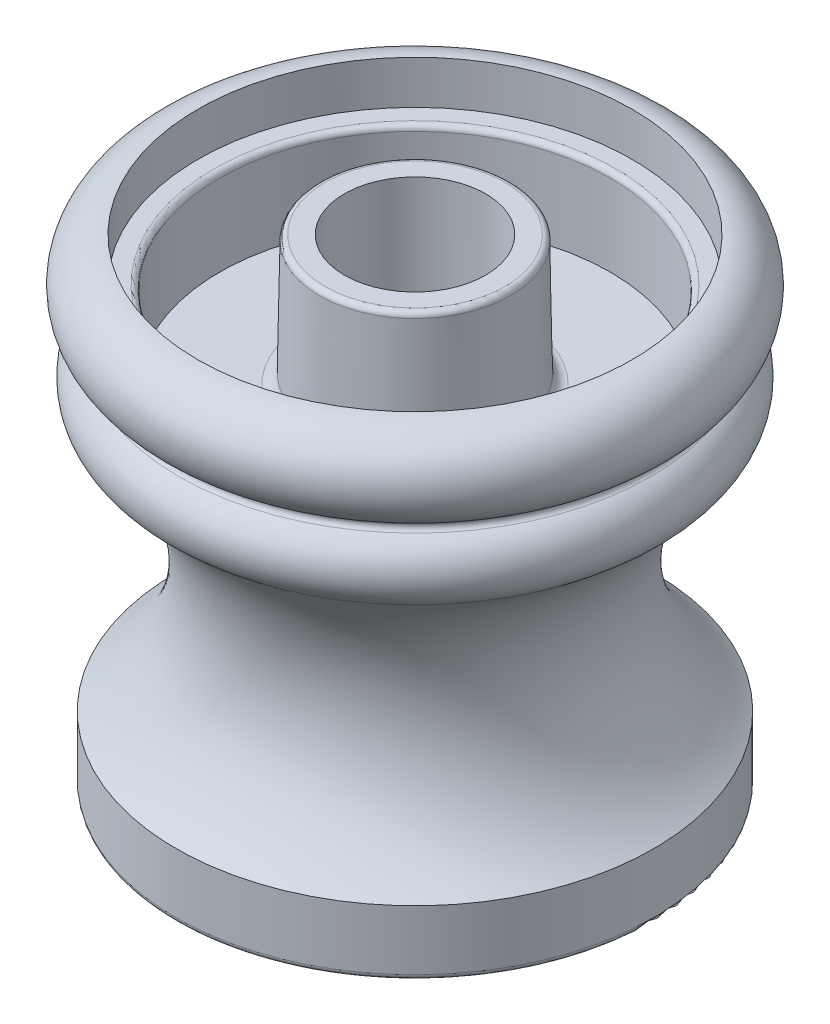
SolidWorks part; units mm, degrees
material "PW50:16:C1:0:1:2:Re:26:"
ref_plane "Plane1" through (0, 0, 0) normal (0, 0, 1) x (1, 0, 0)
ref_plane "Plane2" through (0, 0, 0) normal (0, 1, 0) x (1, 0, 0)
ref_plane "Plane3" through (0, 0, 0) normal (1, 0, 0) x (0, 0, -1)
other "Configuration Table"
sketch "Sketch1" plane through (0, 0, 0) normal (0, 0, 1) x (1, 0, 0)
  line L0 (0, 0) -> (11, 0)
  line L1 (11, 0) -> (11, 3)
  line L2 (0, 0) -> (0, 38.5764) construction
  line L3 (10, 22) -> (0, 22)
  line L4 (0, 22) -> (0, 0)
  arc A0 (11, 3) -> (11, 15) centre (15.5, 9) cw
  arc A1 (11, 15) -> (10.8569, 17.7628) centre (10, 16.3333) ccw
  arc A2 (10.8759, 18.202) -> (10, 22) centre (10, 20) ccw
  arc A3 (10.8569, 17.7628) -> (10.8759, 18.202) centre (10.9854, 17.9773) cw
  point P14 (10, 18)
  dimension "D4" = 8
  dimension "D6" = 10
  dimension "D8" = 10
  dimension "D9" = 0.25
  dimension "D1" = 11
  dimension "D2" = 3
  dimension "D3" = 12
  dimension "D5" = 3
  dimension "D7" = 22
revolve "Base-Revolve" add sketch "Sketch1" angle 360 about L2
hole_wizard "CounterSunk Hole" positions "Sketch7" profile "Sketch6" legacy
sketch "Sketch7" plane through (0, 0, 0) normal (0, -1, 0) x (1, 0, 0)
  point P0 (0, 0)
sketch "Sketch6" plane through (0, 0, 0) normal (1, 0, 0) x (0, 0, -1)
  line L0 (0, 0) -> (0, 12)
  line L1 (0, 12) -> (4.5, 12)
  line L2 (4.5, 12) -> (4.5, 0.546)
  line L3 (4.5, 0.546) -> (6, 0)
  line L4 (6, 0) -> (0, 0)
  line L5 (0, -6.4453) -> (0, 115.525) construction
  line L6 (-4.5, 0.546) -> (-6, 0) construction
  dimension "Diameter" = 9
  dimension "Depth" = 12
  dimension "C-Sink Angle" = 140
  dimension "C-Sink Diameter" = 12
sketch "Sketch2" plane through (0, 22, 0) normal (0, 1, 0) x (-1, 0, 0)
  circle A0 centre (0, 0) radius 10 construction
  circle A1 centre (0, 0) radius 10
extrude "Cut-Extrude1" cut sketch "Sketch2" against normal blind 2
sketch "Sketch3" plane through (0, 20, 0) normal (0, 1, 0) x (-1, 0, 0)
  circle A1 centre (0, 0) radius 9
  circle A2 centre (0, 0) radius 9
  dimension "D1" = 1
extrude "Cut-Extrude2" cut sketch "Sketch3" against normal blind 4
sketch "Sketch4" plane through (0, 16, 0) normal (0, 1, 0) x (-1, 0, 0)
  circle A0 centre (0, 0) radius 4.5
  dimension "D1" = 9
extrude "Boss-Extrude1" add sketch "Sketch4" along normal blind 6 draft 1
sketch "Sketch5" plane through (0, 22, 0) normal (0, 1, 0) x (-1, 0, 0)
  circle A0 centre (0, 0) radius 3.25
  dimension "D1" = 6.5
extrude "Cut-Extrude3" cut sketch "Sketch5" against normal through all
fillet "Fillet1" radius 0.25 3 edges at (0, 0, -11) (0, 22, 4.3953) (0, 20, 9)
fillet "Fillet2" radius 0.5 1 edges at (0, 16, 4.5)
